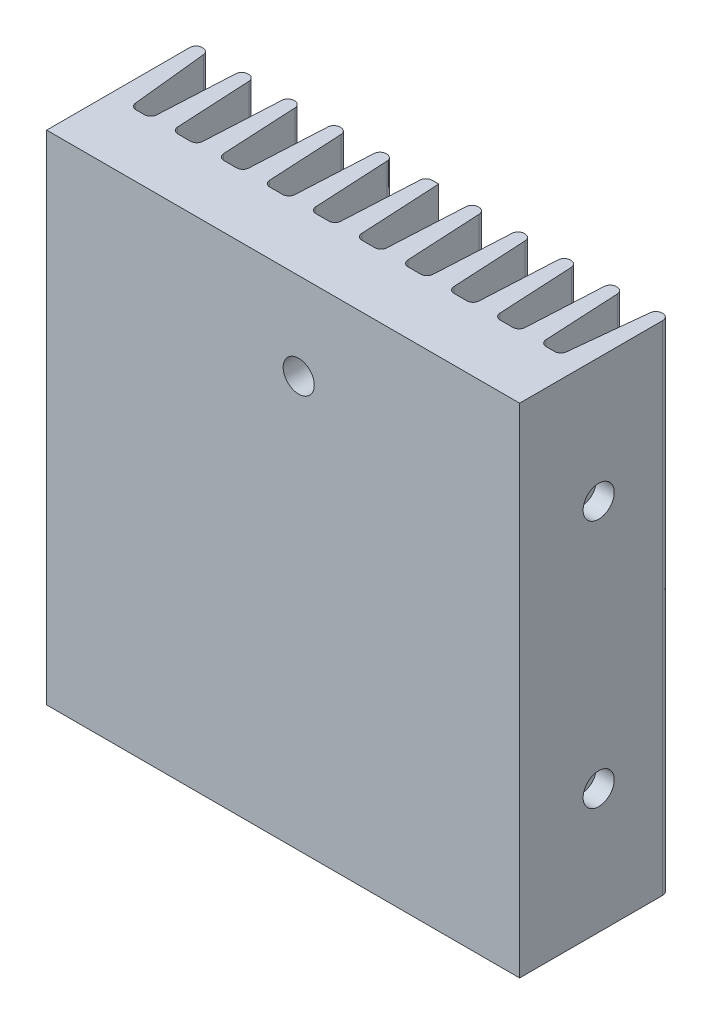
SolidWorks part; units mm, degrees
ref_plane "Front Plane" through (0, 0, 0) normal (0, 0, 1) x (1, 0, 0)
ref_plane "Top Plane" through (0, 0, 0) normal (0, 1, 0) x (1, 0, 0)
ref_plane "Right Plane" through (0, 0, 0) normal (1, 0, 0) x (0, 0, -1)
sketch "Sketch1" plane through (0, 0, 0) normal (0, 1, 0) x (1, 0, 0)
  line L0 (0, 12) -> (0, 0)
  line L1 (0, 0) -> (38, 0)
  line L3 (0, 12) -> (1, 12)
  line L4 (1, 12) -> (1.7357, 5)
  line L26 (1.7357, 5) -> (36.2643, 5)
  line L32 (37, 12) -> (38, 12)
  line L41 (38, 0) -> (38, 12)
  line L42 (36.2643, 5) -> (37, 12)
  dimension "D1" = 38
  dimension "D2" = 12
  dimension "D3" = 6
  dimension "D7" = 6
  dimension "D21" = 1
extrude "Extrude1" add sketch "Sketch1" along normal blind 40
sketch "Sketch3" plane through (0, 40, 0) normal (0, 1, 0) x (1, 0, 0)
  line L0 (3.3331, 5) -> (3.7, 12)
  line L1 (3.7, 12) -> (4.7, 12)
  line L2 (4.7, 12) -> (5.0669, 5)
  line L3 (3.3331, 5) -> (5.0669, 5)
  line L4 (4.2, 12) -> (4.2, -2.4726) construction
  line L5 (0, 12) -> (0, 0) construction
  dimension "D1" = 4.2
  dimension "D2" = 1
extrude "Boss-Extrude1" add sketch "Sketch3" against normal up to surface (40 mm away) up to face at (19, 0, -7.25)
pattern_linear "LPattern1" count 9 spacing 3.7 along (1, 0, 0) of "Boss-Extrude1"
fillet "Fillet1" radius 0.5 20 edges at (36.2643, 20, -5) (30.9669, 20, -5) (29.2331, 20, -5) (27.2669, 20, -5) (25.5331, 20, -5) (23.5669, 20, -5) (21.8331, 20, -5) (19.8669, 20, -5) (18.1331, 20, -5) (16.1669, 20, -5) (14.4331, 20, -5) (12.4669, 20, -5) (10.7331, 20, -5) (8.7669, 20, -5) (7.0331, 20, -5) (1.7357, 20, -5) (5.0669, 20, -5) (3.3331, 20, -5) (34.6669, 20, -5) (32.9331, 20, -5)
fillet "Fillet2" radius 0.5 21 edges at (38, 20, -12) (37, 20, -12) (34.3, 20, -12) (33.3, 20, -12) (30.6, 20, -12) (29.6, 20, -12) (26.9, 20, -12) (25.9, 20, -12) (23.2, 20, -12) (22.2, 20, -12) (18.5, 20, -12) (15.8, 20, -12) (14.8, 20, -12) (12.1, 20, -12) (11.1, 20, -12) (8.4, 20, -12) (7.4, 20, -12) (4.7, 20, -12) (3.7, 20, -12) (1, 20, -12) (0, 20, -12)
sketch "Sketch5" plane through (38, 0, 0) normal (1, 0, 0) x (0, 0, -1)
  line L0 (0, 40) -> (0, 0) construction
  line L1 (5.4477, 40) -> (11.5523, 40) construction
  line L2 (0, 0) -> (11.5, 0) construction
  circle A0 centre (6.35, 30) radius 2.1
  circle A1 centre (6.35, 10) radius 2.1
  point P4 (8.5, 40)
  dimension "D1" = 6.35
  dimension "D2" = 10
  dimension "D3" = 4.2
  dimension "D4" = 10
  dimension "D6" = 4.2
  dimension "D5" = 6.35
extrude "Cut-Extrude1" [suppressed] cut sketch "Sketch5" against normal blind 2.5
hole_wizard "M3x0.5 Tapped Hole1" positions "Sketch7" profile "Sketch6" tap size "M3x0.5" standard "Ansi Metric"
sketch "Sketch7" plane through (38, 0, 0) normal (1, 0, 0) x (0, 0, -1)
  line L0 (0, 40) -> (0, 0) construction
  line L1 (0, 40) -> (11.5, 40) construction
  line L2 (0, 0) -> (11.5, 0) construction
  point P0 (6.35, 30)
  point P6 (6.35, 10)
  dimension "D1" = 6.35
  dimension "D2" = 10
  dimension "D3" = 6.35
  dimension "D4" = 10
sketch "Sketch6" plane through (38, 30, -6.35) normal (0, 1, 0) x (0, 0, -1)
  line L0 (0, 0) -> (0, 7.2511)
  line L1 (0, 7.2511) -> (1.25, 6.5)
  line L2 (1.25, 6.5) -> (1.25, 0)
  line L5 (1.25, 0) -> (0, 0)
  line L10 (0, 7.2511) -> (-1.25, 6.5) construction
  line L11 (0, -6.35) -> (0, 107.95) construction
  dimension "Tap Drill Dia." = 2.5
  dimension "Tap Drill Depth" = 6.5
  dimension "Drill Angle" = 118
cosmetic thread "Hole Thread1" parameters "D1"=5, "D2"=3
cosmetic thread "Hole Thread2" parameters "D1"=5, "D2"=3
hole_wizard "M3x0.5 Tapped Hole2" positions "Sketch9" profile "Sketch8" tap size "M3x0.5" standard "Ansi Metric"
sketch "Sketch9" plane through (0, 0, 0) normal (0, 0, 1) x (1, 0, 0)
  line L0 (38, 40) -> (38, 0) construction
  line L1 (0, 40) -> (38, 40) construction
  point P0 (20.25, 33)
  dimension "D1" = 17.75
  dimension "D2" = 7
sketch "Sketch8" plane through (20.25, 33, 0) normal (1, 0, 0) x (0, -1, 0)
  line L0 (0, 0) -> (0, 5.7511)
  line L1 (0, 5.7511) -> (1.25, 5)
  line L2 (1.25, 5) -> (1.25, 0)
  line L5 (1.25, 0) -> (0, 0)
  line L10 (0, 5.7511) -> (-1.25, 5) construction
  line L11 (0, -6.35) -> (0, 107.95) construction
  dimension "Tap Drill Dia." = 2.5
  dimension "Tap Drill Depth" = 5
  dimension "Drill Angle" = 118
cosmetic thread "Hole Thread3" parameters "D1"=5, "D2"=3
